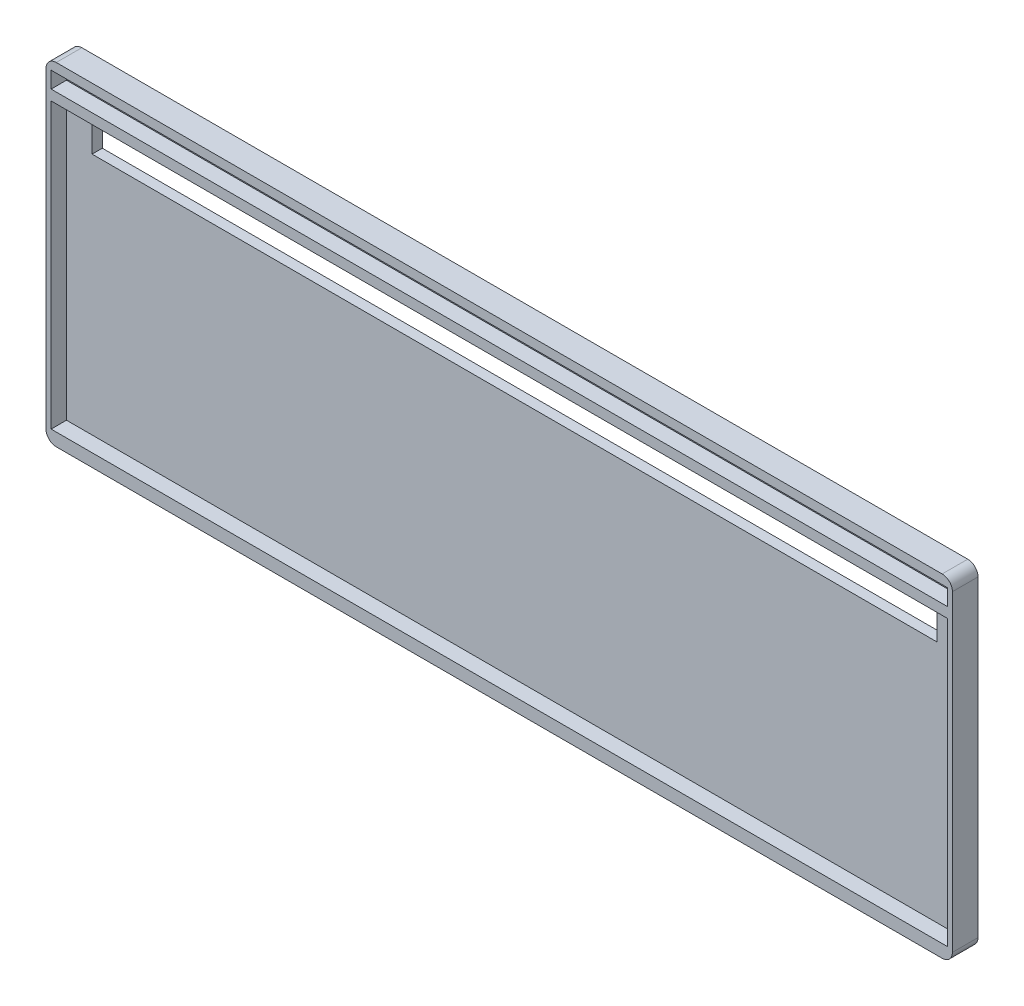
SolidWorks part; units mm, degrees
ref_plane "前视基准面" through (0, 0, 0) normal (0, 0, 1) x (1, 0, 0)
ref_plane "上视基准面" through (0, 0, 0) normal (0, 1, 0) x (1, 0, 0)
ref_plane "右视基准面" through (0, 0, 0) normal (1, 0, 0) x (0, 0, -1)
sketch "草图1" plane through (0, 0, 0) normal (0, 0, 1) x (1, 0, 0)
  line L1 (-88.5, -32.5) -> (88.5, -32.5)
  line L2 (-88.5, -32.5) -> (-88.5, 32.5)
  line L3 (-88.5, 32.5) -> (88.5, 32.5)
  line L4 (88.5, -32.5) -> (88.5, 32.5)
  line L5 (-88.5, -32.5) -> (88.5, 32.5) construction
  line L6 (-88.5, 32.5) -> (88.5, -32.5) construction
  point P0 (0, 0)
  dimension "D1" = 177
  dimension "D2" = 65
extrude "凸台-拉伸1" add sketch "草图1" along normal blind 5
sketch "草图2" plane through (0, 0, 5) normal (0, 0, 1) x (1, 0, 0)
  line L0 (88.5, -32.5) -> (88.5, 32.5) construction
  line L1 (-87.5, -30) -> (87.5, -30)
  line L2 (-87.5, -30) -> (-87.5, 30)
  line L3 (-87.5, 30) -> (87.5, 30)
  line L4 (87.5, -30) -> (87.5, 30)
  line L5 (-87.5, -30) -> (87.5, 30) construction
  line L6 (-87.5, 30) -> (87.5, -30) construction
  line L7 (-88.5, 32.5) -> (88.5, 32.5)
  line L8 (-88.5, 32.5) -> (-88.5, 27.5)
  line L9 (-88.5, 27.5) -> (88.5, 27.5)
  line L10 (88.5, 32.5) -> (88.5, 27.5)
  line L11 (87.5, 30) -> (87.5, 32.5)
  line L12 (-87.5, 30) -> (-87.5, 32.5)
  line L14 (-87.5, -30) -> (87.5, -30)
  line L15 (-87.5, -30) -> (-87.5, 25.5)
  line L16 (-87.5, 25.5) -> (87.5, 25.5)
  line L17 (87.5, -30) -> (87.5, 25.5)
  line L18 (87.5, 30) -> (-87.5, 30)
  line L19 (87.5, 30) -> (87.5, 30.7)
  line L20 (87.5, 30.7) -> (-87.5, 30.7)
  line L21 (-87.5, 30) -> (-87.5, 30.7)
  point P0 (0, 0)
  dimension "D1" = 175
  dimension "D2" = 60
  dimension "D3" = 5
  dimension "D4" = 2
  dimension "D5" = 0.7
extrude "切除-拉伸1" cut sketch "草图2" against normal blind 3 contours L2 L9 L4 L3 | L16 L2 L1 L4 | L11 L20 L12 L3
fillet "圆角1" radius 2 4 edges at (-88.5, -32.5, 2.5) (-88.5, 32.5, 2.5) (88.5, 32.5, 2.5) (88.5, -32.5, 2.5)
sketch "草图4" plane through (0, 0, 2) normal (0, 0, 1) x (1, 0, 0)
  line L0 (87.5, -30) -> (87.5, 25.5) construction
  line L1 (-82.5, 23.5) -> (82.5, 23.5)
  line L2 (-82.5, 23.5) -> (-82.5, 17.5)
  line L3 (-82.5, 17.5) -> (82.5, 17.5)
  line L4 (82.5, 23.5) -> (82.5, 17.5)
  line L5 (-87.5, 25.5) -> (87.5, 25.5) construction
  dimension "D1" = 165
  dimension "D2" = 6
  dimension "D3" = 5
  dimension "D4" = 2
extrude "切除-拉伸2" cut sketch "草图4" against normal blind 3
